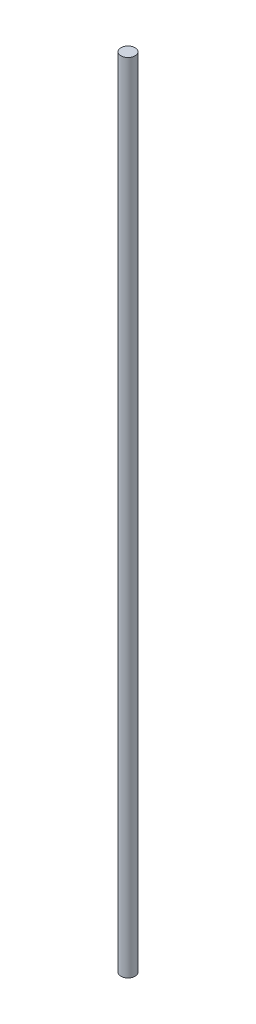
SolidWorks part; units mm, degrees
ref_plane "Front Plane" through (0, 0, 0) normal (0, 0, 1) x (1, 0, 0)
ref_plane "Top Plane" through (0, 0, 0) normal (0, 1, 0) x (1, 0, 0)
ref_plane "Right Plane" through (0, 0, 0) normal (1, 0, 0) x (0, 0, -1)
sketch "Sketch1" plane through (0, 0, 0) normal (0, 1, 0) x (1, 0, 0)
  circle A0 centre (0, 0) radius 6
  dimension "D1" = 12
extrude "Boss-Extrude1" add sketch "Sketch1" along normal blind 680
